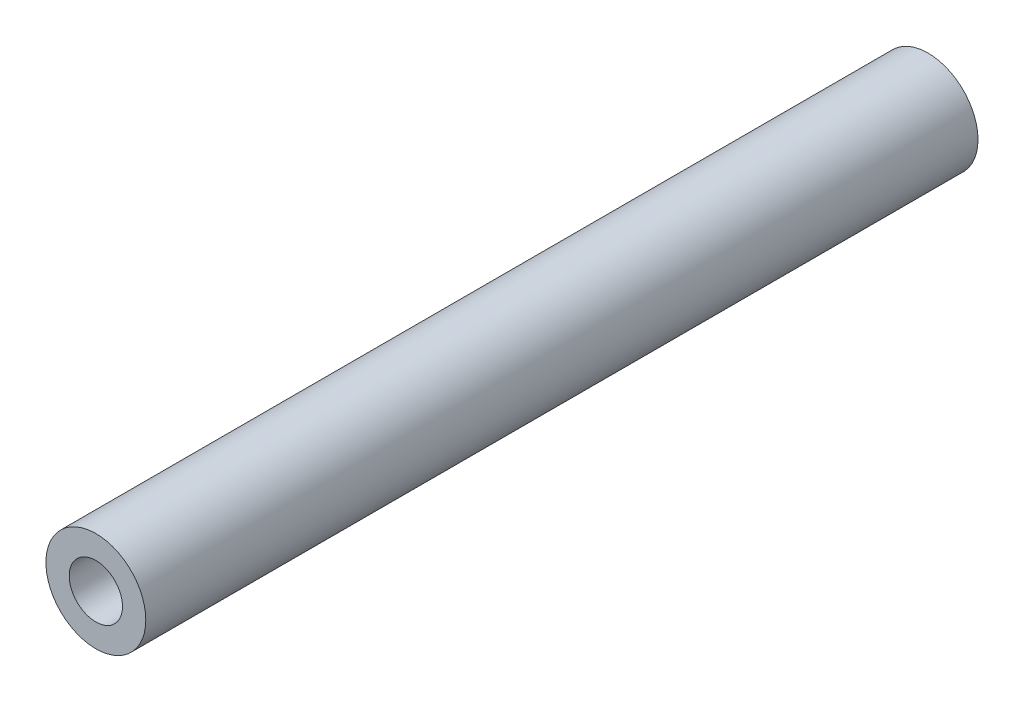
SolidWorks part; units mm, degrees
ref_plane "前视基准面" through (0, 0, 0) normal (0, 0, 1) x (1, 0, 0)
ref_plane "上视基准面" through (0, 0, 0) normal (0, 1, 0) x (1, 0, 0)
ref_plane "右视基准面" through (0, 0, 0) normal (1, 0, 0) x (0, 0, -1)
other "Configuration Table"
sketch "草图1" plane through (0, 0, 0) normal (0, 0, 1) x (1, 0, 0)
  circle A0 centre (0, 0) radius 3
  circle A1 centre (0, 0) radius 1.6
extrude "50mm铝柱" add sketch "草图1" along normal blind 50
